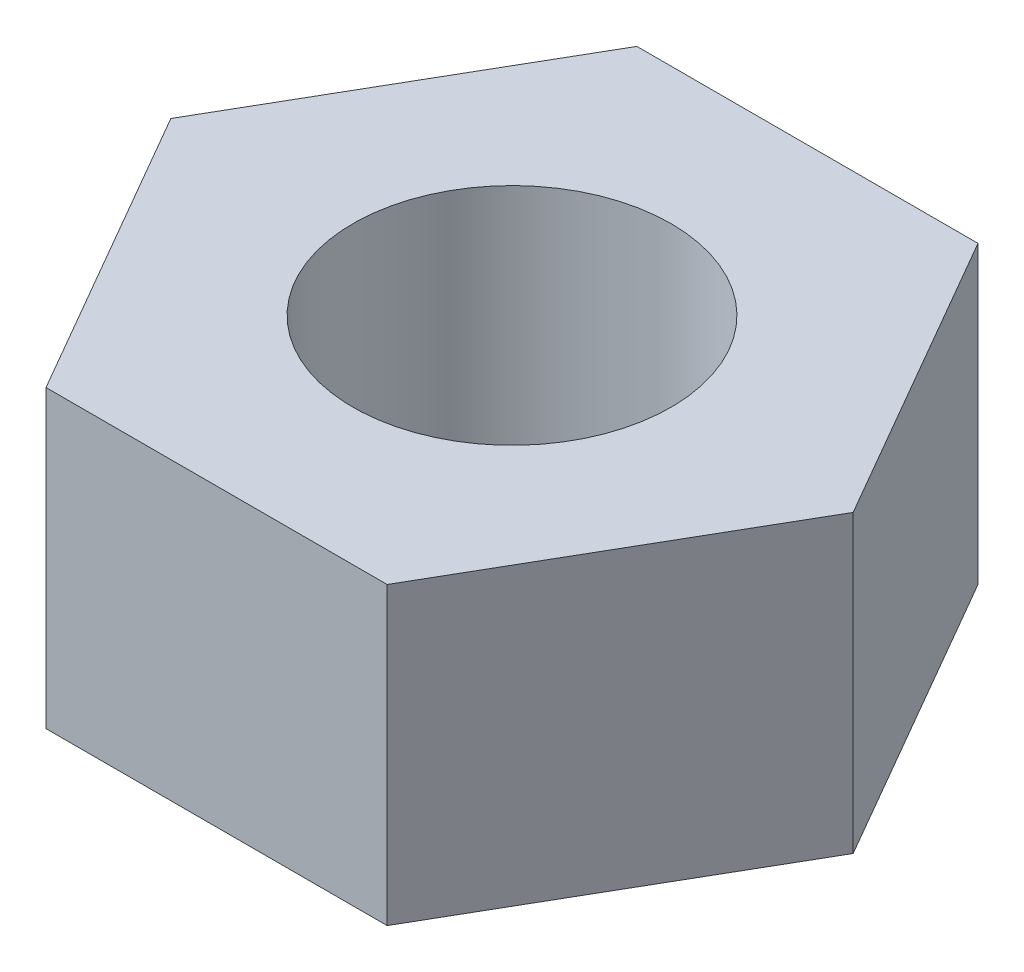
SolidWorks part; units mm, degrees
ref_plane "Front Plane" through (0, 0, 0) normal (0, 0, 1) x (1, 0, 0)
ref_plane "Top Plane" through (0, 0, 0) normal (0, 1, 0) x (1, 0, 0)
ref_plane "Right Plane" through (0, 0, 0) normal (1, 0, 0) x (0, 0, -1)
sketch "Sketch1" plane through (0, 0, 0) normal (0, 1, 0) x (1, 0, 0)
  line L1 (3.7528, 6.5) -> (-3.7528, 6.5)
  line L2 (-3.7528, 6.5) -> (-7.5056, 0)
  line L3 (-7.5056, 0) -> (-3.7528, -6.5)
  line L4 (-3.7528, -6.5) -> (3.7528, -6.5)
  line L5 (3.7528, -6.5) -> (7.5056, 0)
  line L6 (7.5056, 0) -> (3.7528, 6.5)
  circle A0 centre (0, 0) radius 6.5 construction
  circle A1 centre (0, 0) radius 3.5
  dimension "D1" = 13
  dimension "D2" = 7
extrude "Boss-Extrude1" add sketch "Sketch1" along normal blind 6.5
